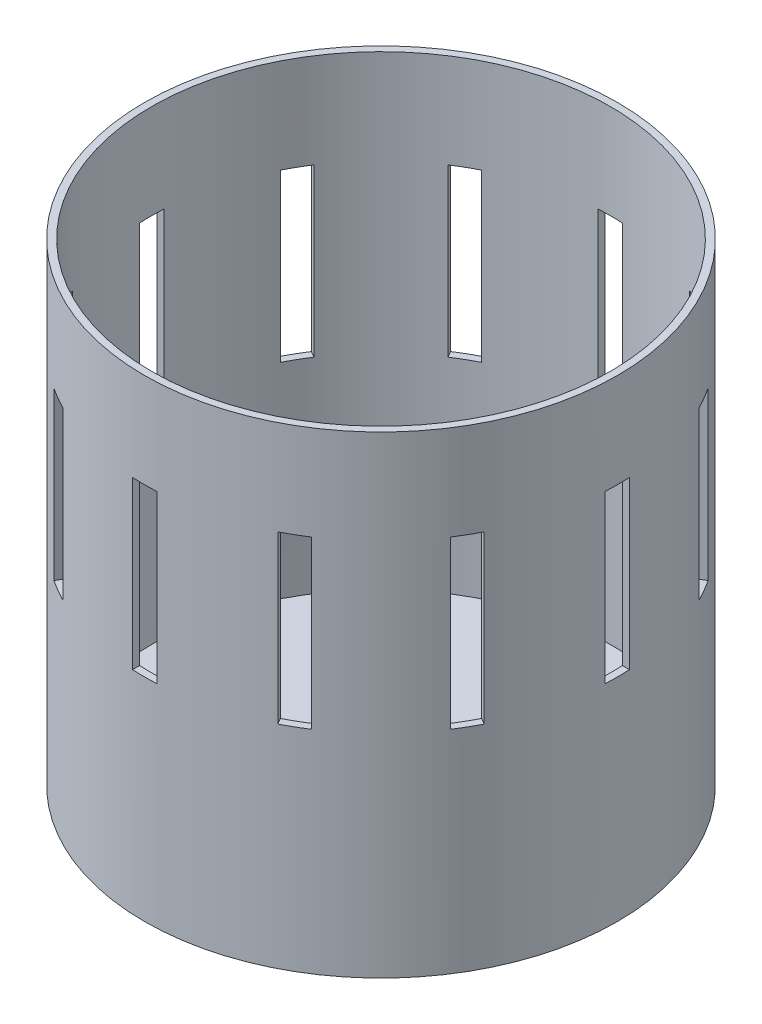
SolidWorks part; units mm, degrees
ref_plane "Alzado" through (0, 0, 0) normal (0, 0, 1) x (1, 0, 0)
ref_plane "Planta" through (0, 0, 0) normal (0, 1, 0) x (1, 0, 0)
ref_plane "Vista lateral" through (0, 0, 0) normal (1, 0, 0) x (0, 0, -1)
sketch "Croquis2" plane through (0, 0, 0) normal (0, 0, 1) x (1, 0, 0)
  line L0 (0, 0) -> (-10, 0)
  line L1 (-10, 0) -> (-10, 5)
  line L2 (-10, 5) -> (-50, 5)
  line L3 (-50, 5) -> (-50, 105)
  line L4 (-50, 105) -> (0, 105)
  line L5 (0, 0) -> (0, 105)
  line L7 (0, 0) -> (0, 105) construction
  dimension "D1" = 50
  dimension "D2" = 10
  dimension "D3" = 100
  dimension "D4" = 5
revolve "Revolución2" add sketch "Croquis2" angle 360 about L7
sketch "Croquis3" plane through (0, 105, 0) normal (0, 1, 0) x (1, 0, 0)
  circle A0 centre (0, 0) radius 48.5
  dimension "D1" = 97
extrude "Cortar-Extruir1" cut sketch "Croquis3" against normal blind 98.5
sketch "Croquis4" plane through (0, 0, 0) normal (0, -1, 0) x (1, 0, 0)
  circle A0 centre (0, 0) radius 1.1
  dimension "D1" = 2.2
extrude "Cortar-Extruir2" cut sketch "Croquis4" against normal blind 98.5
sketch "Croquis6" plane through (0, 0, 0) normal (0, 0, 1) x (1, 0, 0)
  line L0 (0, 0) -> (0, 85) construction
  line L1 (-2.6, 85) -> (2.6, 85)
  line L2 (-2.6, 85) -> (-2.6, 49.8)
  line L3 (-2.6, 49.8) -> (2.6, 49.8)
  line L4 (2.6, 85) -> (2.6, 49.8)
  dimension "D1" = 5.2
  dimension "D2" = 35.2
  dimension "D3" = 85
extrude "Cortar-Extruir3" cut sketch "Croquis6" against normal blind 98.5
pattern_circular "MatrizC1" count 12 over 360 about axis through (0, 0, 0) along (0, 1, 0) of "Cortar-Extruir3"
